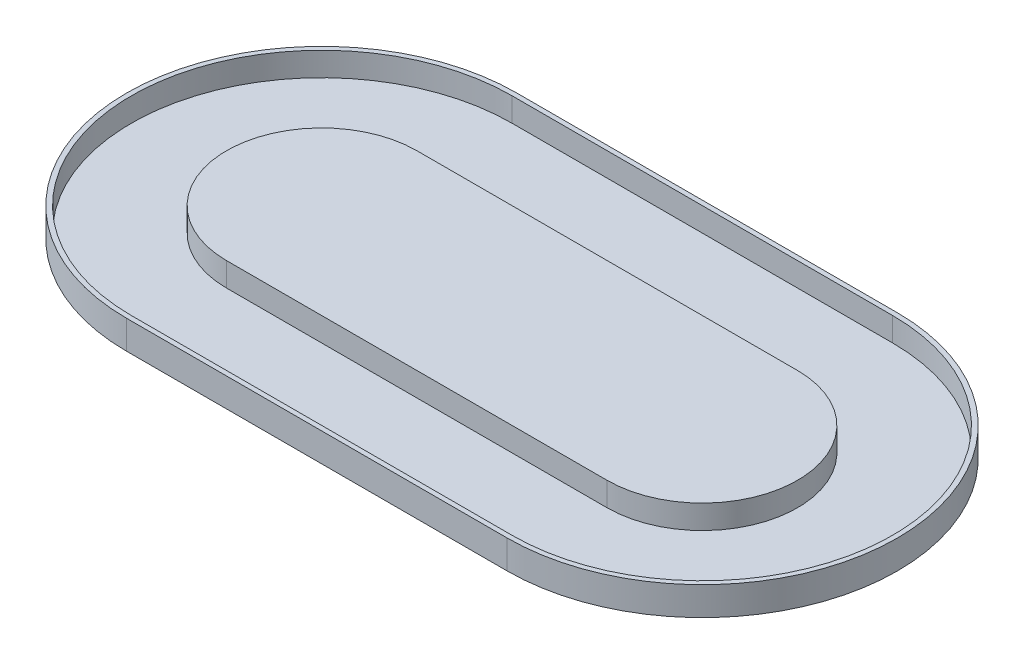
SolidWorks part; units mm, degrees
ref_plane "Front Plane" through (0, 0, 0) normal (0, 0, 1) x (1, 0, 0)
ref_plane "Top Plane" through (0, 0, 0) normal (0, 1, 0) x (1, 0, 0)
ref_plane "Right Plane" through (0, 0, 0) normal (1, 0, 0) x (0, 0, -1)
sketch "Sketch1" plane through (0, 0, 0) normal (0, 1, 0) x (1, 0, 0)
  line L0 (-4000, 2000) -> (4000, 2000)
  line L1 (-4000, -4000) -> (4000, -4000)
  line L3 (-4000, 4000) -> (4000, 4000)
  line L6 (-8000, 0) -> (-4000, 0) construction
  line L7 (-4000, -2000) -> (4000, -2000)
  line L10 (6000, 0) -> (4000, 0) construction
  arc A2 (4000, -2000) -> (4000, 2000) centre (4000, 0) ccw
  arc A3 (-4000, 2000) -> (-4000, -2000) centre (-4000, 0) ccw
  arc A4 (4000, -4000) -> (4000, 4000) centre (4000, 0) ccw
  arc A7 (-4000, 4000) -> (-4000, -4000) centre (-4000, 0) ccw
  point P0 (0, 0)
  dimension "D1" = 8000
  dimension "D2" = 8000
  dimension "D5" = 2000
  dimension "D6" = 2000
extrude "Boss-Extrude1" add sketch "Sketch1" along normal blind 100
sketch "Sketch2" plane through (0, 100, 0) normal (0, 1, 0) x (1, 0, 0)
  line L0 (4000, 4100) -> (-4000, 4100)
  line L1 (-4000, -4100) -> (4000, -4100)
  line L2 (-4000, -4000) -> (4000, -4000)
  line L3 (4000, 4000) -> (-4000, 4000)
  line L4 (-4000, -4000) -> (4000, -4000)
  line L5 (4000, 4000) -> (-4000, 4000)
  arc A0 (-4000, 4100) -> (-4000, -4100) centre (-4000, 0) ccw
  arc A1 (4000, -4100) -> (4000, 4100) centre (4000, 0) ccw
  arc A2 (-4000, 4000) -> (-4000, -4000) centre (-4000, 0) ccw
  arc A3 (4000, -4000) -> (4000, 4000) centre (4000, 0) ccw
  arc A4 (-4000, 4000) -> (-4000, -4000) centre (-4000, 0) ccw
  arc A5 (4000, -4000) -> (4000, 4000) centre (4000, 0) ccw
  dimension "D1" = 0
  dimension "D2" = 100
extrude "Boss-Extrude2" add sketch "Sketch2" along normal blind 500 and the other way blind 100
sketch "Sketch3" plane through (0, 100, 0) normal (0, 1, 0) x (1, 0, 0)
  line L0 (4000, 2000) -> (-4000, 2000) construction
  line L1 (4000, 2000) -> (-4000, 2000)
  line L2 (-4000, -4000) -> (4000, -4000)
  line L3 (4000, 4000) -> (-4000, 4000)
  line L4 (-4000, -4000) -> (4000, -4000)
  line L5 (4000, 4000) -> (-4000, 4000)
  line L6 (-4000, -2000) -> (4000, -2000) construction
  line L7 (-4000, -2000) -> (4000, -2000)
  line L8 (-4000, -1900) -> (4000, -1900)
  line L9 (4000, 1900) -> (-4000, 1900)
  arc A0 (4000, -2000) -> (4000, 2000) centre (4000, 0) ccw construction
  arc A1 (-4000, 2000) -> (-4000, -2000) centre (-4000, 0) ccw construction
  arc A2 (-4000, 4000) -> (-4000, -4000) centre (-4000, 0) ccw
  arc A3 (4000, -4000) -> (4000, 4000) centre (4000, 0) ccw
  arc A4 (-4000, 4000) -> (-4000, -4000) centre (-4000, 0) ccw
  arc A5 (4000, -4000) -> (4000, 4000) centre (4000, 0) ccw
  arc A6 (4000, -2000) -> (4000, 2000) centre (4000, 0) ccw
  arc A7 (-4000, 2000) -> (-4000, -2000) centre (-4000, 0) ccw
  arc A8 (-4000, 1900) -> (-4000, -1900) centre (-4000, 0) ccw
  arc A9 (4000, -1900) -> (4000, 1900) centre (4000, 0) ccw
  line M13 (-4000, 2000) -> (4000, 2000)
  arc M14 (4000, 2000) -> (4000, -2000) centre (4000, 0) cw
  line M15 (4000, -2000) -> (-4000, -2000)
  arc M16 (-4000, -2000) -> (-4000, 2000) centre (-4000, 0) cw
  dimension "D1" = 0
  dimension "D2" = 100
extrude "Boss-Extrude3" add sketch "Sketch3" along normal blind 500 and the other way blind 100 contours A9 L8 A8 L9 M13 M16 M15 M14 | L1 A7 L7 A6
